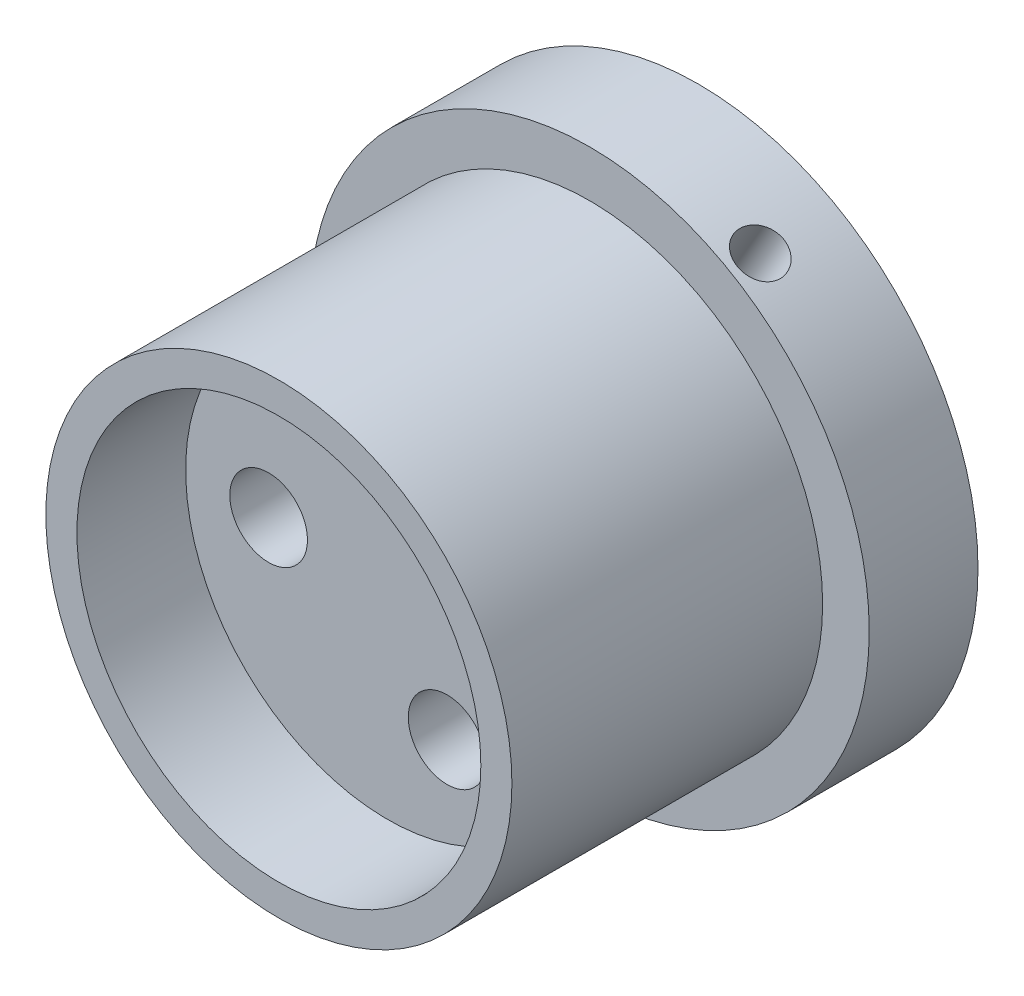
SolidWorks part; units mm, degrees
ref_plane "Front Plane" through (0, 0, 0) normal (0, 0, 1) x (1, 0, 0)
ref_plane "Top Plane" through (0, 0, 0) normal (0, 1, 0) x (1, 0, 0)
ref_plane "Right Plane" through (0, 0, 0) normal (1, 0, 0) x (0, 0, -1)
sketch "Sketch1" plane through (0, 0, 0) normal (0, 0, 1) x (1, 0, 0)
  circle A0 centre (0, 0) radius 15
  dimension "D1" = 30
extrude "Boss-Extrude1" add sketch "Sketch1" along normal blind 20
sketch "Sketch2" plane through (0, 0, 20) normal (0, 0, 1) x (1, 0, 0)
  circle A0 centre (0, 0) radius 10.95
  dimension "D1" = 21.9
extrude "Boss-Extrude2" add sketch "Sketch2" along normal blind 3.5 contours A0
sketch "Sketch4" plane through (0, 0, 0) normal (0, 0, -1) x (-1, 0, 0)
  circle A0 centre (0, 0) radius 3.05
  dimension "D1" = 6.1
extrude "Cut-Extrude1" cut sketch "Sketch4" against normal blind 4.1
sketch "Sketch5" plane through (0, 0, 4.1) normal (0, 0, -1) x (-1, 0, 0)
  circle A0 centre (0, 0) radius 1.5
  dimension "D1" = 3
extrude "Cut-Extrude2" cut sketch "Sketch5" along direction (0, 0, -1) on the side against the normal blind 4 contours A0
sketch "Sketch7" plane through (0, 0, 23.5) normal (0, 0, 1) x (1, 0, 0)
  circle A0 centre (0, 0) radius 3
  circle A1 centre (0, 0) radius 10.95
  dimension "D1" = 21.9
extrude "Boss-Extrude3" add sketch "Sketch7" along normal blind 11
sketch "Sketch9" plane through (0, 0, 34.5) normal (0, 0, 1) x (1, 0, 0)
  line L0 (0, 0) -> (7, 0) construction
  circle A0 centre (7, 0) radius 1.5
  circle A1 centre (-3.5, -6.0622) radius 1.5
  circle A2 centre (-3.5, 6.0622) radius 1.5
  dimension "D2" = 3
  dimension "D1" = 7
  dimension "D3" = 3
extrude "Cut-Extrude4" cut sketch "Sketch9" against normal through all
sketch "Sketch12" plane through (0, 0, 0) normal (0, 0, -1) x (-1, 0, 0)
  circle A0 centre (0, 0) radius 18
  circle A1 centre (3.5, 6.0622) radius 3.25
  circle A2 centre (3.5, -6.0622) radius 3.25
  circle A3 centre (-7, 0) radius 3.25
  circle A4 centre (0, 0) radius 3.05
  dimension "D1" = 36
extrude "Boss-Extrude4" add sketch "Sketch12" along normal blind 7
sketch "Sketch13" plane through (0, 0, 0) normal (1, 0, 0) x (0, 0, -1)
  line L0 (7, 0) -> (-3, 0) construction
  circle A0 centre (2, 0) radius 1.5
  dimension "D1" = 3
extrude "Cut-Extrude9" cut sketch "Sketch13" against normal blind 17 from offset 5 offset against normal yes
pattern_circular "CirPattern1" count 3 over 360 about axis through (0, 0, 0) along (0, 0, 1) of "Cut-Extrude9"
sketch "Sketch15" plane through (0, 0, 20) normal (0, 0, 1) x (1, 0, 0)
  circle A0 centre (0, 0) radius 13
  circle M2 centre (0, 0) radius 10.95
  dimension "D1" = 26
extrude "Cut-Extrude12" cut sketch "Sketch15" along normal blind 15 and the other way through all contours M2 | A0 M2
sketch "Sketch17" plane through (0, 0, 0) normal (0, 0, 1) x (1, 0, 0)
  circle A0 centre (0, 0) radius 13
extrude "Boss-Extrude6" add sketch "Sketch17" along normal blind 20 from offset 7 offset against normal yes
sketch "Sketch19" plane through (0, 0, -7) normal (0, 0, -1) x (-1, 0, 0)
  circle A0 centre (7.66, 0) radius 2.5
  circle A1 centre (-3.83, -6.6338) radius 2.5
  circle A2 centre (-3.83, 6.6338) radius 2.5
  point P2 (0, 0)
  point P4 (-4.109, 6.481)
  point P13 (12.7478, 18.7674)
  dimension "D1" = 5
  dimension "D3" = 7.66
  dimension "D4" = 7.66
  dimension "D2" = 3
extrude "Cut-Extrude13" cut sketch "Sketch19" against normal through all
sketch "Sketch20" plane through (0, 0, -7) normal (0, 0, -1) x (-1, 0, 0)
  circle A0 centre (7.66, 0) radius 5
  circle A1 centre (-3.83, 6.6338) radius 5
  circle A2 centre (-3.83, -6.6338) radius 5
  circle M1 centre (7.66, 0) radius 2.5
  circle M2 centre (-3.83, -6.6338) radius 2.5
  circle M3 centre (-3.83, 6.6338) radius 2.5
  dimension "D1" = 10
extrude "Cut-Extrude14" cut sketch "Sketch20" against normal blind 5 contours A0 M1 | A1 M3 | A2 M2
